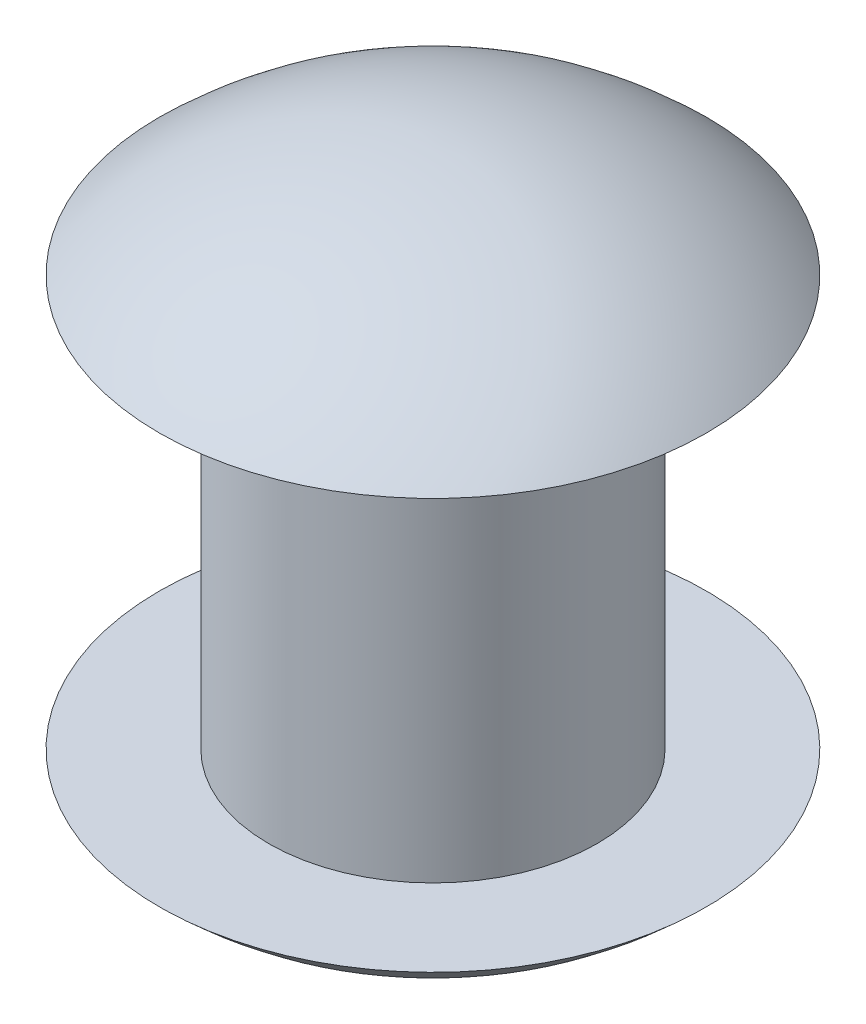
SolidWorks part; units mm, degrees
material "2024-O"
ref_plane "Front Plane" through (0, 0, 0) normal (0, 0, 1) x (1, 0, 0)
ref_plane "Top Plane" through (0, 0, 0) normal (0, 1, 0) x (1, 0, 0)
ref_plane "Right Plane" through (0, 0, 0) normal (1, 0, 0) x (0, 0, -1)
sketch "Sketch1" plane through (0, 0, 0) normal (0, 0, 1) x (1, 0, 0)
  line L7 (0, 5.75) -> (0, -5.75)
  line L8 (3, 3.75) -> (5, 3.75)
  line L9 (3, 3.75) -> (3, -3.75)
  line L10 (3, -3.75) -> (5, -3.75)
  arc A6 (5, -3.75) -> (0, -5.75) centre (0, 1.5) cw
  arc A7 (0, 5.75) -> (5, 3.75) centre (0, -1.5) cw
  point P1 (0, 0)
  dimension "D2" = 7.5
  dimension "D3" = 3
  dimension "D4" = 3.75
  dimension "D1" = 11.5
  dimension "D5" = 5
revolve "Revolve3" add sketch "Sketch1" angle 360 about L7
equation "\"altura do rebite\"= 7.5"
equation "\"D2@Sketch1\"=\"altura do rebite\""
equation "\"Diametro interno-rebite\"= 3"
equation "\"raio interno-rebite\"= 3"
equation "\"D3@Sketch1\"=\"raio interno-rebite\""
equation "\"Diametro externo-rebite\"= \"raio interno-rebite\" + 2"
equation "\"Altura externa-rebite\"= \"altura do rebite\" + 4"
equation "\"D4@Sketch1\"=\"altura do rebite\"/2"
equation "\"a\"=28.1345"
equation "\"D1@Sketch1\"=\"Altura externa-rebite\""
equation "\"D5@Sketch1\"=\"Diametro externo-rebite\""
